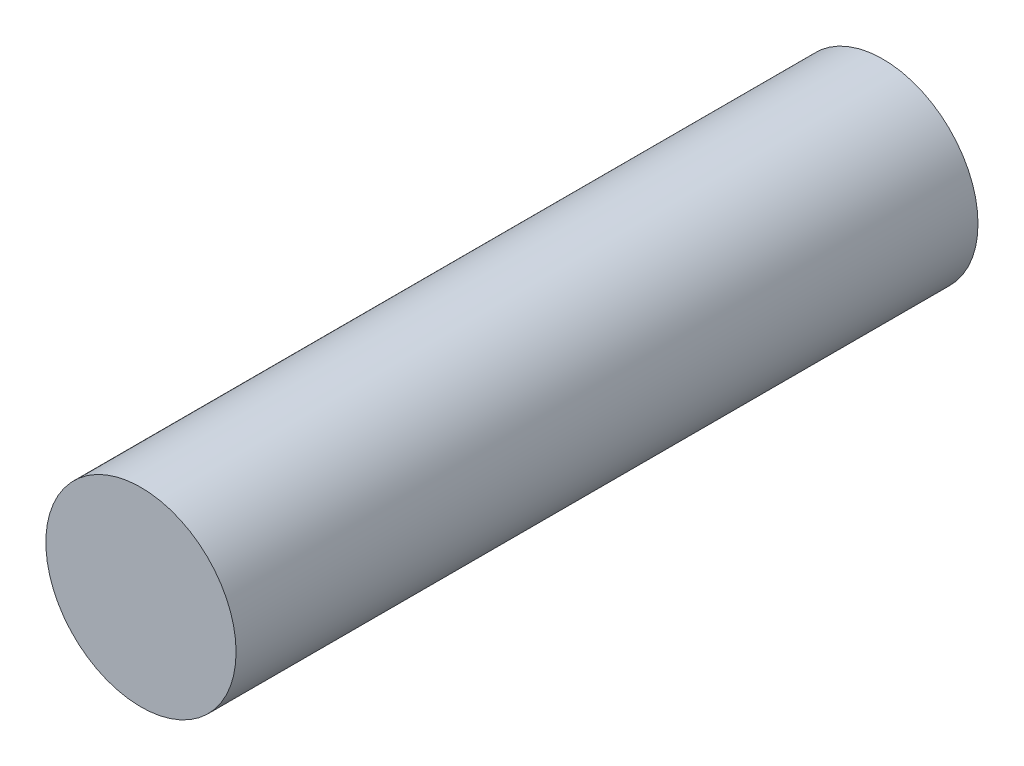
SolidWorks part; units mm, degrees
material "AISI 1045 Steel, cold drawn"
ref_plane "Front Plane" through (0, 0, 0) normal (0, 0, 1) x (1, 0, 0)
ref_plane "Top Plane" through (0, 0, 0) normal (0, 1, 0) x (1, 0, 0)
ref_plane "Right Plane" through (0, 0, 0) normal (1, 0, 0) x (0, 0, -1)
sketch "Sketch1" plane through (0, 0, 0) normal (0, 0, 1) x (1, 0, 0)
  circle A0 centre (0, 0) radius 10
  dimension "D1" = 20
extrude "Boss-Extrude1" add sketch "Sketch1" along normal mid plane 78 contours A0
